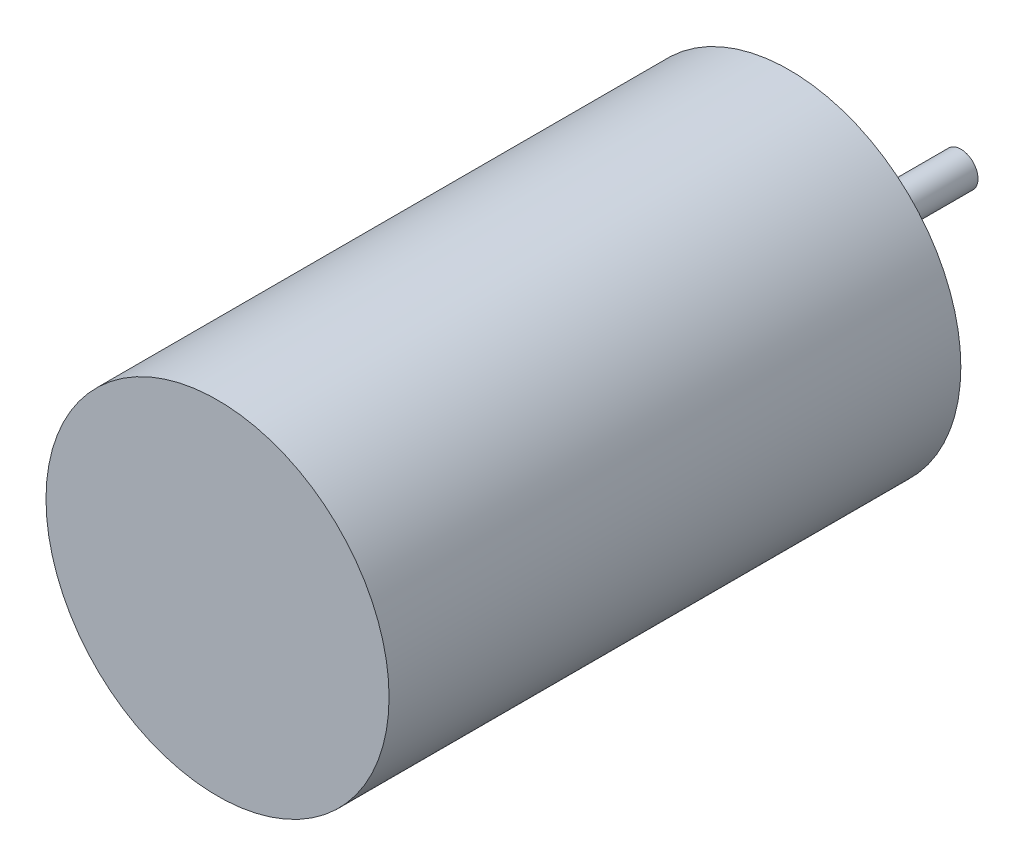
SolidWorks part; units mm, degrees
ref_plane "Front Plane" through (0, 0, 0) normal (0, 0, 1) x (1, 0, 0)
ref_plane "Top Plane" through (0, 0, 0) normal (0, 1, 0) x (1, 0, 0)
ref_plane "Right Plane" through (0, 0, 0) normal (1, 0, 0) x (0, 0, -1)
sketch "Sketch1" plane through (0, 0, 0) normal (0, 0, 1) x (1, 0, 0)
  circle A0 centre (0, 0) radius 15
  dimension "D1" = 30
extrude "Boss-Extrude1" add sketch "Sketch1" along normal blind 50
sketch "Sketch2" plane through (0, 0, 0) normal (0, 0, -1) x (-1, 0, 0)
  circle A0 centre (0, 0) radius 1.5
  dimension "D1" = 3
extrude "Boss-Extrude2" add sketch "Sketch2" along normal blind 15
